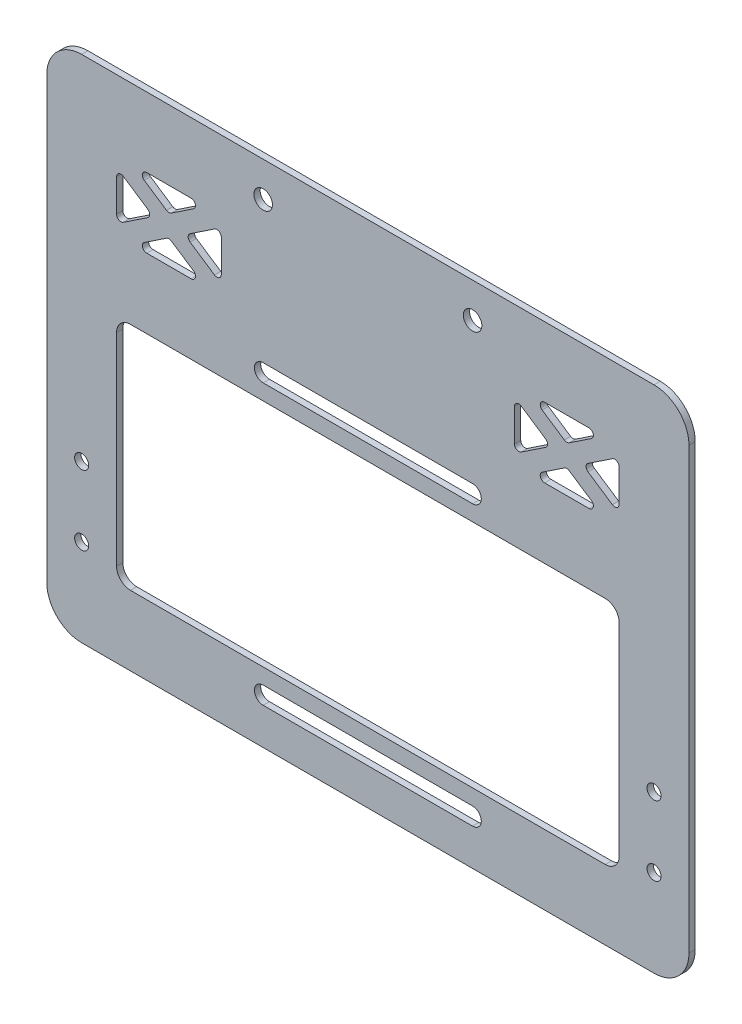
SolidWorks part; units mm, degrees
ref_plane "Front Plane" through (0, 0, 0) normal (0, 0, 1) x (1, 0, 0)
ref_plane "Top Plane" through (0, 0, 0) normal (0, 1, 0) x (1, 0, 0)
ref_plane "Right Plane" through (0, 0, 0) normal (1, 0, 0) x (0, 0, -1)
sketch "Sketch1" plane through (0, 0, 0) normal (0, 0, 1) x (1, 0, 0)
  line L1 (-116.84, 92.71) -> (116.84, 92.71)
  line L2 (-116.84, 92.71) -> (-116.84, -92.71)
  line L3 (-116.84, -92.71) -> (116.84, -92.71)
  line L4 (116.84, 92.71) -> (116.84, -92.71)
  line L5 (-116.84, 92.71) -> (116.84, -92.71) construction
  line L6 (-116.84, -92.71) -> (116.84, 92.71) construction
  line L7 (-86.36, 16.51) -> (86.36, 16.51)
  line L8 (-91.44, 11.43) -> (-91.44, -62.23)
  line L9 (-86.36, -67.31) -> (86.36, -67.31)
  line L10 (91.44, 11.43) -> (91.44, -62.23)
  line L11 (-91.44, 16.51) -> (91.44, -67.31) construction
  line L12 (-91.44, -67.31) -> (91.44, 16.51) construction
  arc A0 (86.36, -67.31) -> (91.44, -62.23) centre (86.36, -62.23) ccw
  arc A1 (86.36, 16.51) -> (91.44, 11.43) centre (86.36, 11.43) cw
  arc A2 (-91.44, 11.43) -> (-86.36, 16.51) centre (-86.36, 11.43) cw
  arc A3 (-86.36, -67.31) -> (-91.44, -62.23) centre (-86.36, -62.23) cw
  point P0 (0, 0)
  point P5 (0, -25.4)
  dimension "D7" = 5.08
  dimension "D1" = 25.4
  dimension "D2" = 185.42
  dimension "D3" = 182.88
  dimension "D4" = 83.82
  dimension "D5" = 25.4
  dimension "D6" = 233.68
extrude "Boss-Extrude1" add sketch "Sketch1" along normal blind 2.286
sketch "Sketch2" plane through (0, 0, 2.286) normal (0, 0, 1) x (1, 0, 0)
  line L0 (38.1, 25.4) -> (-38.1, 25.4) construction
  line L1 (38.1, 22.225) -> (-38.1, 22.225)
  line L2 (38.1, 28.575) -> (-38.1, 28.575)
  line L3 (-91.44, 11.43) -> (-91.44, -62.23) construction
  line L4 (-91.44, -25.4) -> (91.44, -25.4) construction
  line L5 (-91.44, 11.43) -> (-91.44, -62.23) construction
  line L6 (91.44, -62.23) -> (91.44, 11.43) construction
  line L7 (38.1, -76.2) -> (-38.1, -76.2) construction
  line L8 (38.1, -73.025) -> (-38.1, -73.025)
  line L9 (38.1, -79.375) -> (-38.1, -79.375)
  arc A0 (38.1, 22.225) -> (38.1, 28.575) centre (38.1, 25.4) ccw
  arc A1 (-38.1, 28.575) -> (-38.1, 22.225) centre (-38.1, 25.4) ccw
  arc A2 (38.1, -73.025) -> (38.1, -79.375) centre (38.1, -76.2) cw
  arc A3 (-38.1, -79.375) -> (-38.1, -73.025) centre (-38.1, -76.2) cw
  point P2 (0, 25.4)
  point P7 (-91.44, -25.4)
  point P19 (0, -76.2)
  dimension "D1" = 76.2
  dimension "D2" = 50.8
  dimension "D3" = 6.35
extrude "Cut-Extrude1" cut sketch "Sketch2" against normal through all
hole_wizard "1/4 Clearance Hole2" positions "Sketch8" profile "Sketch7" hole size "1/4" standard "ANSI Inch" end condition through all
sketch "Sketch8" plane through (0, 0, 2.286) normal (0, 0, 1) x (1, 0, 0)
  line L3 (-38.1, 80.01) -> (38.1, 80.01) construction
  line L5 (116.84, 92.71) -> (-116.84, 92.71) construction
  line L6 (-34.925, 80.01) -> (34.925, 80.01) construction
  point P0 (-38.1, 80.01)
  point P2 (38.1, 80.01)
  point P17 (0, 80.01)
  dimension "D1" = 76.2
  dimension "D2" = 12.7
sketch "Sketch7" plane through (-38.1, 80.01, 2.286) normal (1, 0, 0) x (0, -1, 0)
  line L0 (0, 0) -> (0, 2.286)
  line L1 (0, 2.286) -> (3.3782, 2.286)
  line L2 (3.3782, 2.286) -> (3.3782, 0)
  line L5 (3.3782, 0) -> (0, 0)
  line L11 (0, -6.35) -> (0, 107.95) construction
  dimension "Thru Hole Dia." = 6.7564
  dimension "Thru Hole Depth" = 2.286
fillet "Fillet1" radius 12.7 4 edges at (-116.84, 92.71, 1.143) (116.84, 92.71, 1.143) (-116.84, -92.71, 1.143) (116.84, -92.71, 1.143)
sketch "Sketch9" plane through (0, 0, 2.286) normal (0, 0, 1) x (1, 0, 0)
  line L0 (-104.14, -92.71) -> (104.14, -92.71) construction
  line L1 (-116.84, 80.01) -> (-116.84, -80.01) construction
  line L2 (116.84, -80.01) -> (116.84, 80.01) construction
  circle A0 centre (-104.14, -60.96) radius 2.5527
  circle A1 centre (104.14, -60.96) radius 2.5527
  circle A2 centre (104.14, -35.56) radius 2.5527
  circle A3 centre (-104.14, -35.56) radius 2.5527
  dimension "D3" = 5.1054
  dimension "D1" = 25.4
  dimension "D2" = 25.4
  dimension "D4" = 31.75
  dimension "D5" = 12.7
  dimension "D6" = 12.7
  dimension "D7" = 31.75
extrude "Cut-Extrude2" cut sketch "Sketch9" against normal through all
sketch "Sketch10" plane through (0, 0, 2.286) normal (0, 0, 1) x (1, 0, 0)
  line L0 (104.14, 92.71) -> (-104.14, 92.71) construction
  line L1 (-91.44, 67.31) -> (-53.34, 67.31)
  line L2 (-91.44, 67.31) -> (-91.44, 41.91)
  line L3 (-91.44, 41.91) -> (-53.34, 41.91)
  line L4 (-53.34, 67.31) -> (-53.34, 41.91)
  line L5 (-91.44, 67.31) -> (-53.34, 41.91) construction
  line L6 (-91.44, 41.91) -> (-53.34, 67.31) construction
  line L7 (53.34, 67.31) -> (91.44, 67.31)
  line L8 (53.34, 67.31) -> (53.34, 41.91)
  line L9 (53.34, 41.91) -> (91.44, 41.91)
  line L10 (91.44, 67.31) -> (91.44, 41.91)
  line L11 (53.34, 67.31) -> (91.44, 41.91) construction
  line L12 (53.34, 41.91) -> (91.44, 67.31) construction
  line L13 (-116.84, 80.01) -> (-116.84, -80.01) construction
  line L14 (116.84, -80.01) -> (116.84, 80.01) construction
  line L15 (-93.2012, 64.6682) -> (-55.1012, 39.2682)
  line L16 (-89.6788, 39.2682) -> (-51.5788, 64.6682)
  line L17 (55.1012, 39.2682) -> (93.2012, 64.6682)
  line L18 (51.5788, 64.6682) -> (89.6788, 39.2682)
  line L19 (-89.6788, 69.9518) -> (-51.5788, 44.5518)
  line L20 (-93.2012, 44.5518) -> (-55.1012, 69.9518)
  line L21 (51.5788, 44.5518) -> (89.6788, 69.9518)
  line L22 (55.1012, 69.9518) -> (93.2012, 44.5518)
  point P0 (-72.39, 54.61)
  point P5 (72.39, 54.61)
  dimension "D1" = 38.1
  dimension "D2" = 25.4
  dimension "D3" = 25.4
  dimension "D4" = 25.4
  dimension "D5" = 25.4
  dimension "D6" = 3.175
  dimension "D7" = 3.175
extrude "Cut-Extrude3" cut sketch "Sketch10" against normal through all contours L19 L20 L1 | L2 L20 L15 | L16 L3 L15 | L16 L19 L4 | L18 L17 L9 | L8 L21 L18 | L7 L22 L21 | L17 L22 L10
fillet "Fillet2" radius 1.5875 24 edges at (91.44, 63.4941, 1.143) (91.44, 45.7259, 1.143) (78.1138, 54.61, 1.143) (85.7162, 67.31, 1.143) (59.0638, 67.31, 1.143) (72.39, 58.4259, 1.143) (66.6662, 54.61, 1.143) (53.34, 63.4941, 1.143) (53.34, 45.7259, 1.143) (85.7162, 41.91, 1.143) (72.39, 50.7941, 1.143) (59.0638, 41.91, 1.143) (-78.1138, 54.61, 1.143) (-91.44, 63.4941, 1.143) (-91.44, 45.7259, 1.143) (-59.0638, 67.31, 1.143) (-85.7162, 67.31, 1.143) (-72.39, 58.4259, 1.143) (-53.34, 63.4941, 1.143) (-53.34, 45.7259, 1.143) (-66.6662, 54.61, 1.143) (-72.39, 50.7941, 1.143) (-59.0638, 41.91, 1.143) (-85.7162, 41.91, 1.143)
